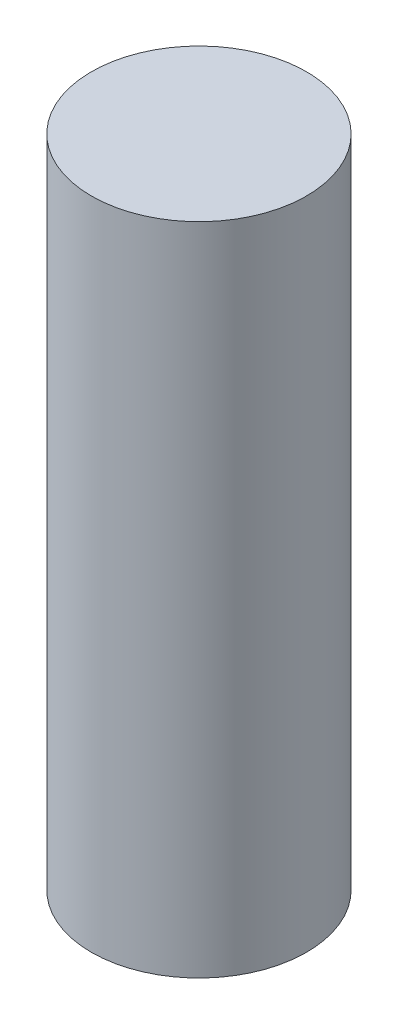
SolidWorks part; units mm, degrees
ref_plane "Front Plane" through (0, 0, 0) normal (0, 0, 1) x (1, 0, 0)
ref_plane "Top Plane" through (0, 0, 0) normal (0, 1, 0) x (1, 0, 0)
ref_plane "Right Plane" through (0, 0, 0) normal (1, 0, 0) x (0, 0, -1)
sketch "Sketch1" plane through (0, 0, 0) normal (0, 1, 0) x (1, 0, 0)
  circle A0 centre (0, 0) radius 11.5
  dimension "D1" = 23
extrude "Boss-Extrude1" add sketch "Sketch1" along normal blind 70
